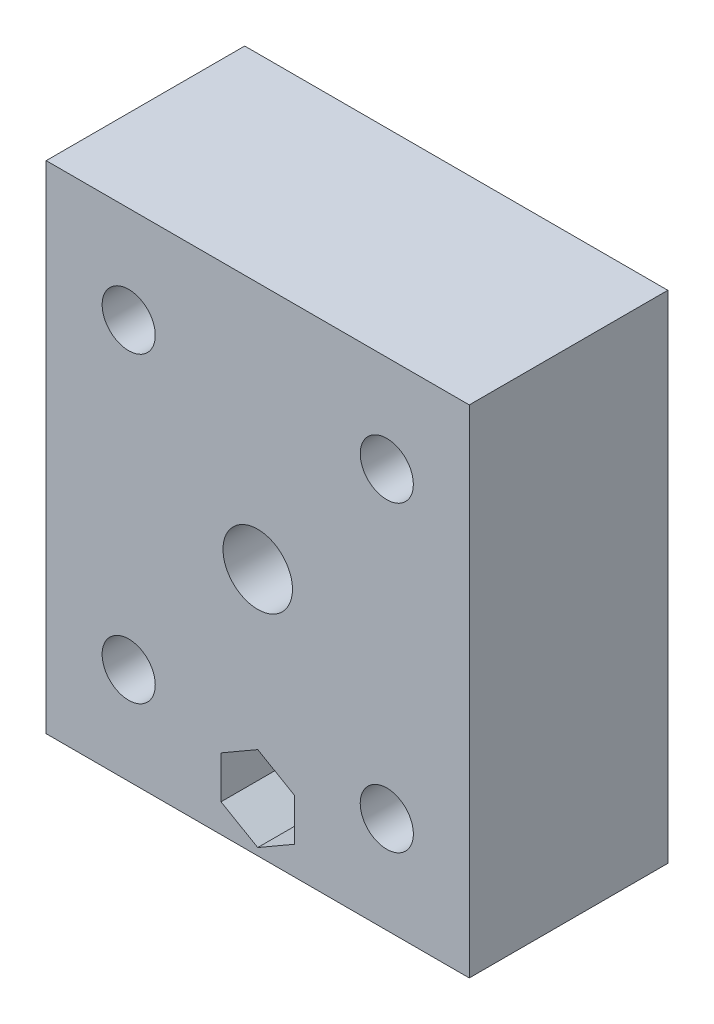
SolidWorks part; units mm, degrees
ref_plane "Front Plane" through (0, 0, 0) normal (0, 0, 1) x (1, 0, 0)
ref_plane "Top Plane" through (0, 0, 0) normal (0, 1, 0) x (1, 0, 0)
ref_plane "Right Plane" through (0, 0, 0) normal (1, 0, 0) x (0, 0, -1)
sketch "Sketch1" plane through (0, 0, 0) normal (0, 0, 1) x (1, 0, 0)
  line L0 (0, 25) -> (0, -25) construction
  line L1 (21.3115, 25) -> (-21.3115, 25)
  line L2 (21.3115, 25) -> (21.3115, -25)
  line L3 (21.3115, -25) -> (-21.3115, -25)
  line L4 (-21.3115, 25) -> (-21.3115, -25)
  line L5 (21.3115, 25) -> (-21.3115, -25) construction
  line L6 (21.3115, -25) -> (-21.3115, 25) construction
  line L7 (-21.3115, 0) -> (21.3115, 0) construction
  circle A0 centre (-13, -15.25) radius 2.677
  circle A1 centre (13, -15.25) radius 2.677
  circle A2 centre (13, 15.25) radius 2.677
  circle A3 centre (-13, 15.25) radius 2.677
  point P0 (0, 0)
  dimension "D1" = 30.5
  dimension "D2" = 26
  dimension "D3" = 50
extrude "Boss-Extrude1" add sketch "Sketch1" along normal blind 20
sketch "Sketch2" plane through (0, 0, 0) normal (0, 0, 1) x (1, 0, 0)
  circle A0 centre (0, 0) radius 5.025
  dimension "D1" = 10.05
extrude "Cut-Extrude2" cut sketch "Sketch2" along normal blind 3
sketch "Sketch3" plane through (0, 0, 0) normal (0, 0, -1) x (-1, 0, 0)
  circle A0 centre (0, -20) radius 2.2
  dimension "D1" = 4.4
  dimension "D2" = 20
extrude "Cut-Extrude3" cut sketch "Sketch3" against normal blind 10
sketch "Sketch5" plane through (0, 0, 0) normal (0, 0, -1) x (-1, 0, 0)
  line L1 (0, -15.7276) -> (-3.7, -17.8638)
  line L2 (-3.7, -17.8638) -> (-3.7, -22.1362)
  line L3 (-3.7, -22.1362) -> (0, -24.2724)
  line L4 (0, -24.2724) -> (3.7, -22.1362)
  line L5 (3.7, -22.1362) -> (3.7, -17.8638)
  line L6 (3.7, -17.8638) -> (0, -15.7276)
  circle A0 centre (0, -20) radius 3.7 construction
  dimension "D1" = 3.7
extrude "Cut-Extrude4" cut sketch "Sketch5" against normal through all from offset 7 offset against normal yes
sketch "Sketch6" plane through (0, 0, 0) normal (0, 0, 1) x (1, 0, 0)
  circle A0 centre (0, 0) radius 3.5
  dimension "D1" = 7
extrude "Cut-Extrude5" cut sketch "Sketch6" along normal through all
